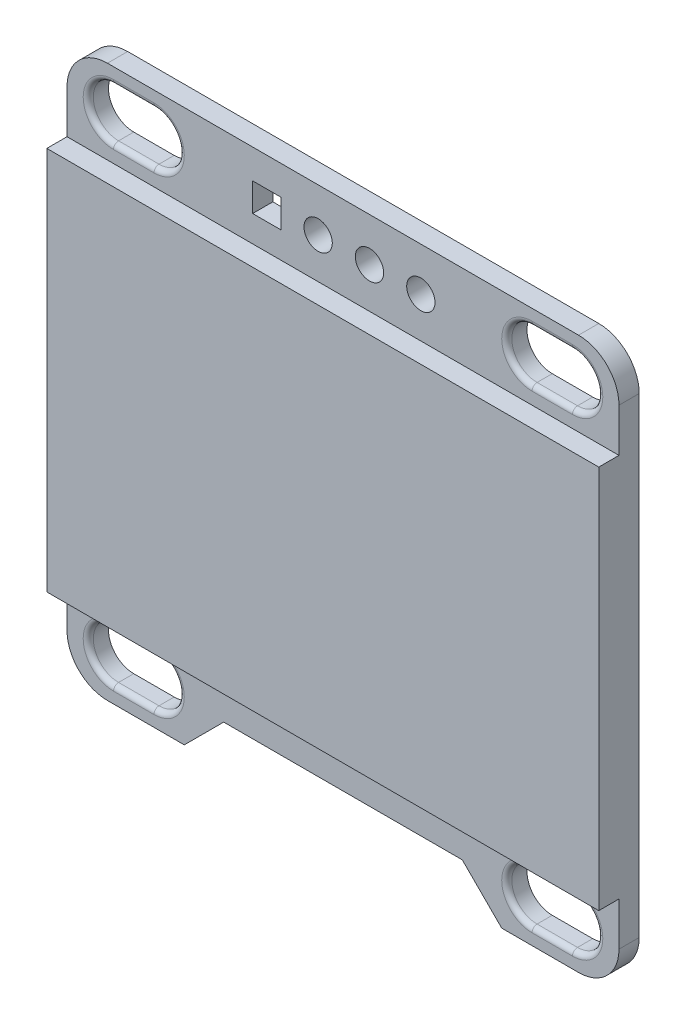
SolidWorks part; units mm, degrees
ref_plane "Front Plane" through (0, 0, 0) normal (0, 0, 1) x (1, 0, 0)
ref_plane "Top Plane" through (0, 0, 0) normal (0, 1, 0) x (1, 0, 0)
ref_plane "Right Plane" through (0, 0, 0) normal (1, 0, 0) x (0, 0, -1)
sketch "Sketch1" plane through (0, 0, 0) normal (0, 0, 1) x (1, 0, 0)
  line L1 (13.65, -13.65) -> (-13.65, -13.65)
  line L2 (13.65, -13.65) -> (13.65, 13.65)
  line L3 (13.65, 13.65) -> (-13.65, 13.65)
  line L4 (-13.65, -13.65) -> (-13.65, 13.65)
  line L5 (13.65, -13.65) -> (-13.65, 13.65) construction
  line L6 (13.65, 13.65) -> (-13.65, -13.65) construction
  point P0 (0, 0)
  dimension "D1" = 27.3
  dimension "D2" = 27.3
extrude "Boss-Extrude1" add sketch "Sketch1" along normal blind 1 contours L3 L4 L1 L2
fillet "Fillet1" radius 2 4 edges at (-13.65, -13.65, 0.5) (13.65, -13.65, 0.5) (13.65, 13.65, 0.5) (-13.65, 13.65, 0.5)
sketch "Sketch2" plane through (0, 0, 1) normal (0, 0, 1) x (1, 0, 0)
  line L0 (-11.35, 11.6) -> (-9.35, 11.6) construction
  line L1 (-11.35, 12.85) -> (-9.35, 12.85)
  line L2 (-11.35, 10.35) -> (-9.35, 10.35)
  line L3 (11.35, 11.6) -> (9.35, 11.6) construction
  line L4 (11.35, 10.35) -> (9.35, 10.35)
  line L5 (11.35, 12.85) -> (9.35, 12.85)
  line L6 (-11.35, -11.6) -> (-9.35, -11.6) construction
  line L7 (-11.35, -10.35) -> (-9.35, -10.35)
  line L8 (-11.35, -12.85) -> (-9.35, -12.85)
  line L9 (11.35, -11.6) -> (9.35, -11.6) construction
  line L10 (11.35, -12.85) -> (9.35, -12.85)
  line L11 (11.35, -10.35) -> (9.35, -10.35)
  line L12 (-13.65, -11.65) -> (-13.65, 11.65) construction
  line L13 (11.65, 13.65) -> (-11.65, 13.65) construction
  arc A0 (-11.35, 12.85) -> (-11.35, 10.35) centre (-11.35, 11.6) ccw
  arc A1 (-9.35, 10.35) -> (-9.35, 12.85) centre (-9.35, 11.6) ccw
  arc A2 (11.35, 10.35) -> (11.35, 12.85) centre (11.35, 11.6) ccw
  arc A3 (9.35, 12.85) -> (9.35, 10.35) centre (9.35, 11.6) ccw
  arc A4 (-11.35, -10.35) -> (-11.35, -12.85) centre (-11.35, -11.6) ccw
  arc A5 (-9.35, -12.85) -> (-9.35, -10.35) centre (-9.35, -11.6) ccw
  arc A6 (11.35, -12.85) -> (11.35, -10.35) centre (11.35, -11.6) ccw
  arc A7 (9.35, -10.35) -> (9.35, -12.85) centre (9.35, -11.6) ccw
  point P2 (-10.35, 11.6)
  point P7 (10.35, 11.6)
  point P14 (-10.35, -11.6)
  point P21 (10.35, -11.6)
  dimension "D3" = 2
  dimension "D1" = 23.2
  dimension "D2" = 20.7
  dimension "D4" = 2.5
  dimension "D5" = 2
  dimension "D6" = 2.5
  dimension "D7" = 3.3
  dimension "D8" = 2.05
extrude "Cut-Extrude1" cut sketch "Sketch2" against normal blind 2
sketch "Sketch5" plane through (0, 0, 1) normal (0, 0, 1) x (1, 0, 0)
  line L0 (-13.65, -11.65) -> (-13.65, 11.65) construction
  line L1 (-13.65, 9.5) -> (13.65, 9.5)
  line L2 (-13.65, 9.5) -> (-13.65, -9.5)
  line L3 (-13.65, -9.5) -> (13.65, -9.5)
  line L4 (13.65, 9.5) -> (13.65, -9.5)
  line L5 (13.65, -11.65) -> (13.65, 11.65) construction
  line L6 (-11.35, 10.35) -> (-9.35, 10.35) construction
  dimension "D1" = 19
  dimension "D2" = 0.85
extrude "Boss-Extrude2" add sketch "Sketch5" along normal blind 1
sketch "Sketch3" plane through (0, 0, 1) normal (0, 0, 1) x (1, 0, 0)
  line L0 (-7.85, -13.65) -> (-5.9, -11.7)
  line L1 (11.65, -13.65) -> (-11.65, -13.65) construction
  line L2 (-5.9, -11.7) -> (5.9, -11.7)
  line L3 (5.9, -11.7) -> (7.85, -13.65)
  line L4 (7.85, -13.65) -> (-7.85, -13.65)
  arc A0 (-9.35, -12.85) -> (-9.35, -10.35) centre (-9.35, -11.6) ccw construction
  arc A2 (9.35, -10.35) -> (9.35, -12.85) centre (9.35, -11.6) ccw construction
  arc A3 (-11.35, -10.35) -> (-11.35, -12.85) centre (-11.35, -11.6) ccw construction
  dimension "D2" = 1.5
  dimension "D1" = 1.5
  dimension "D3" = 0.1
  dimension "D4" = 45
  dimension "D5" = 45
extrude "Cut-Extrude2" cut sketch "Sketch3" against normal blind 2
fillet "Fillet2" radius 0.25 16 edges at (-8.1, -11.6, 1) (-10.35, -12.85, 1) (-12.6, -11.6, 1) (12.6, -11.6, 1) (10.35, -12.85, 1) (8.1, -11.6, 1) (12.6, 11.6, 1) (10.35, 10.35, 1) (8.1, 11.6, 1) (-8.1, 11.6, 1) (-10.35, 10.35, 1) (-12.6, 11.6, 1) (-10.35, -10.35, 1) (10.35, -10.35, 1) (10.35, 12.85, 1) (-10.35, 12.85, 1)
sketch "Sketch7" plane through (0, 0, 0) normal (0, 0, -1) x (-1, 0, 0)
  line L0 (-5.7472, 11.5) -> (6.111, 11.5) construction
  line L1 (-13.65, 9.5) -> (13.65, 9.5) construction
  line L2 (-13.65, -11.65) -> (-13.65, 11.65) construction
  line L4 (4.47, 10.8) -> (3.07, 10.8)
  line L5 (4.47, 10.8) -> (4.47, 12.2)
  line L6 (4.47, 12.2) -> (3.07, 12.2)
  line L7 (3.07, 10.8) -> (3.07, 12.2)
  line L8 (4.47, 10.8) -> (3.07, 12.2) construction
  line L9 (4.47, 12.2) -> (3.07, 10.8) construction
  circle A0 centre (-3.85, 11.5) radius 0.7
  circle A1 centre (-1.31, 11.5) radius 0.7
  circle A2 centre (1.23, 11.5) radius 0.7
  point P12 (3.77, 11.5)
  dimension "D2" = 9.8
  dimension "D5" = 2.54
  dimension "D6" = 1.4
  dimension "D7" = 1.4
  dimension "D8" = 1.4
  dimension "D1" = 2
  dimension "D3" = 2.54
  dimension "D4" = 2.54
  dimension "D9" = 1.4
  dimension "D10" = 1.4
extrude "Cut-Extrude3" cut sketch "Sketch7" against normal blind 1
